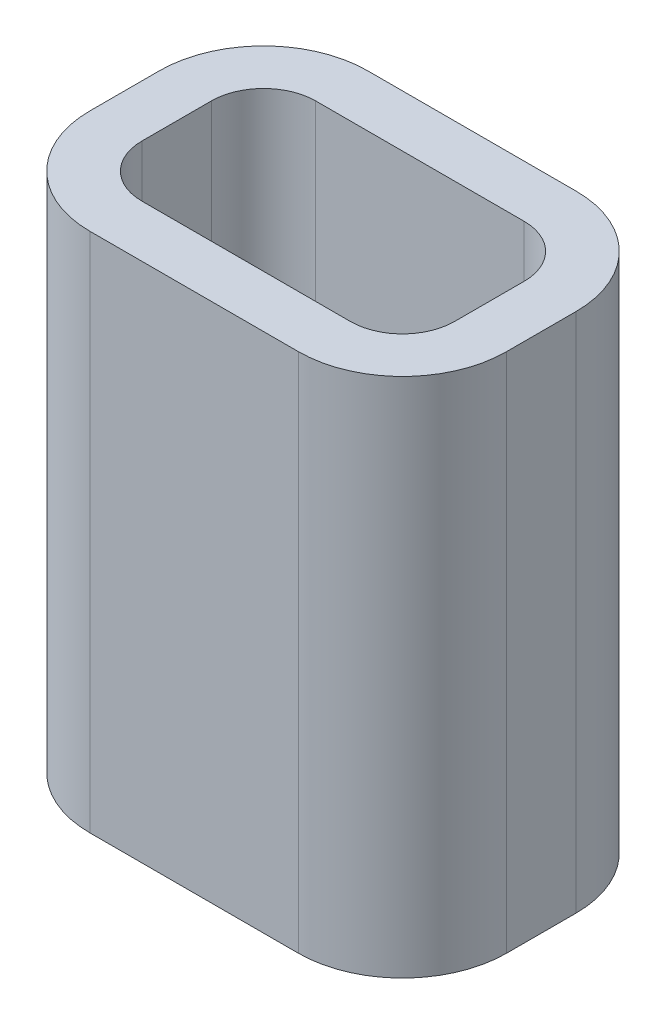
SolidWorks part; units mm, degrees
ref_plane "Alzado" through (0, 0, 0) normal (0, 0, 1) x (1, 0, 0)
ref_plane "Planta" through (0, 0, 0) normal (0, 1, 0) x (1, 0, 0)
ref_plane "Vista lateral" through (0, 0, 0) normal (1, 0, 0) x (0, 0, -1)
sketch "Croquis1" plane through (0, 0, 0) normal (0, 1, 0) x (1, 0, 0)
  line L0 (-6, 8) -> (6, 8)
  line L1 (-6, -5) -> (6, -5)
  line L2 (-9, -2) -> (-9, 2)
  line L3 (-6, 5) -> (6, 5)
  line L4 (9, -2) -> (9, 2)
  line L5 (-9, -5) -> (9, 5) construction
  line L6 (-9, 5) -> (9, -5) construction
  line L7 (12, -2) -> (12, 2)
  line L8 (-6, -8) -> (6, -8)
  line L9 (-12, -2) -> (-12, 2)
  arc A0 (6, 5) -> (9, 2) centre (6, 2) cw
  arc A1 (6, -5) -> (9, -2) centre (6, -2) ccw
  arc A2 (-6, -5) -> (-9, -2) centre (-6, -2) cw
  arc A3 (-9, 2) -> (-6, 5) centre (-6, 2) cw
  arc A4 (6, 8) -> (12, 2) centre (6, 2) cw
  arc A5 (6, -8) -> (12, -2) centre (6, -2) ccw
  arc A6 (-6, -8) -> (-12, -2) centre (-6, -2) cw
  arc A7 (-12, 2) -> (-6, 8) centre (-6, 2) cw
  point P0 (0, 0)
  dimension "D3" = 3
  dimension "D1" = 10
  dimension "D2" = 18
  dimension "D4" = 3
extrude "Saliente-Extruir1" add sketch "Croquis1" along normal blind 30
sketch "Croquis3" plane through (0, 0, -8) normal (0, 0, -1) x (-1, 0, 0)
  line L0 (0, 15) -> (0, 0) construction
  line L1 (-2.4468, 12.9911) -> (2.4468, 12.9911)
  line L2 (-2.4468, 12.9911) -> (-2.4468, 17.0089)
  line L3 (-2.4468, 17.0089) -> (2.4468, 17.0089)
  line L4 (2.4468, 12.9911) -> (2.4468, 17.0089)
  line L5 (-2.4468, 12.9911) -> (2.4468, 17.0089) construction
  line L6 (-2.4468, 17.0089) -> (2.4468, 12.9911) construction
  point P0 (0, 15)
extrude "Saliente-Extruir2" add sketch "Croquis3" along normal blind 3
sketch "Croquis5" plane through (0, 0, 0) normal (0, -1, 0) x (1, 0, 0)
  line L14 (6, -5) -> (-6, -5) construction
  line L15 (-9, -2) -> (-9, 2) construction
  line L16 (9, 2) -> (9, -2) construction
  line L17 (-6, 5) -> (6, 5) construction
  line L18 (6, -5) -> (-6, -5)
  line L19 (-9, -2) -> (-9, 2)
  line L20 (9, 2) -> (9, -2)
  line L21 (-6, 5) -> (6, 5)
  arc A14 (-9, -2) -> (-6, -5) centre (-6, -2) ccw construction
  arc A15 (-6, 5) -> (-9, 2) centre (-6, 2) ccw construction
  arc A16 (9, 2) -> (6, 5) centre (6, 2) ccw construction
  arc A17 (6, -5) -> (9, -2) centre (6, -2) ccw construction
  arc A18 (-9, -2) -> (-6, -5) centre (-6, -2) ccw
  arc A19 (-6, 5) -> (-9, 2) centre (-6, 2) ccw
  arc A20 (9, 2) -> (6, 5) centre (6, 2) ccw
  arc A21 (6, -5) -> (9, -2) centre (6, -2) ccw
extrude "Saliente-Extruir3" add sketch "Croquis5" against normal blind 1
